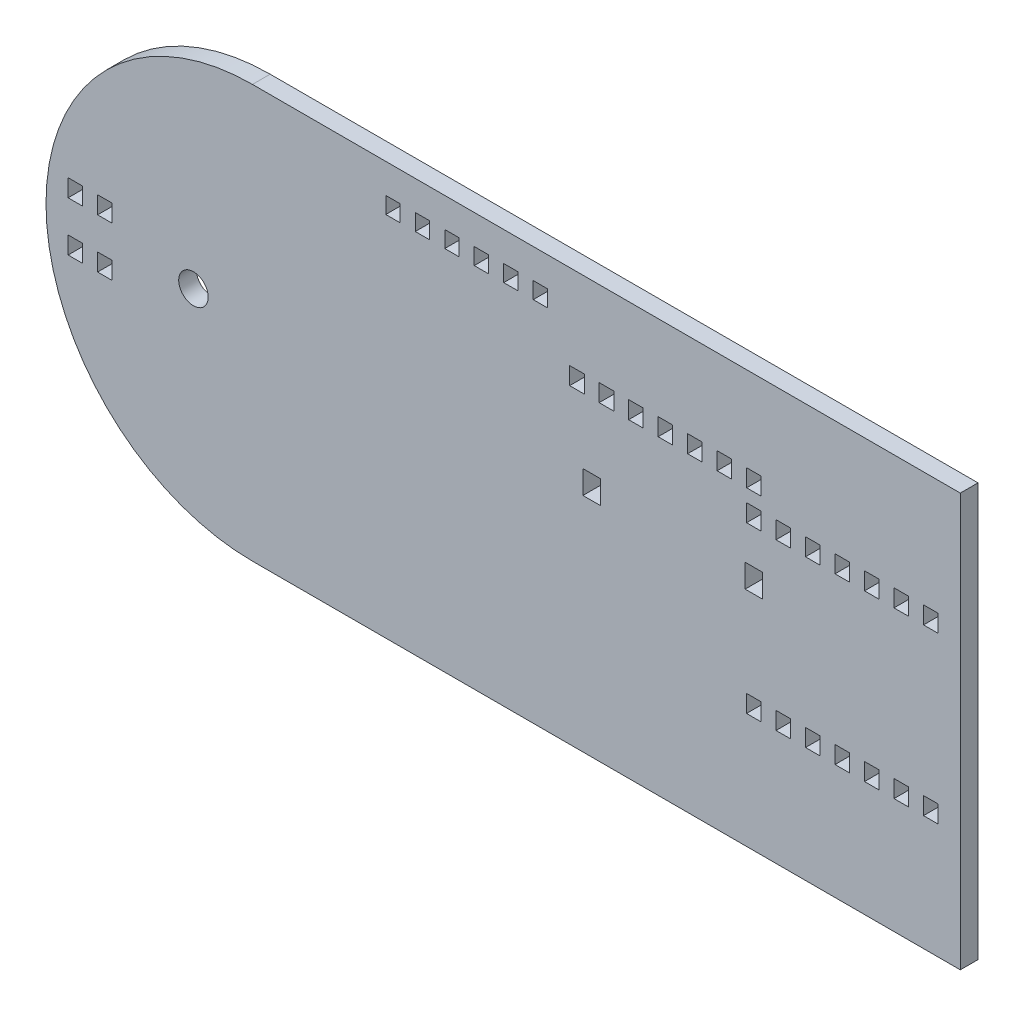
SolidWorks part; units mm, degrees
ref_plane "Plan de face" through (0, 0, 0) normal (0, 0, 1) x (1, 0, 0)
ref_plane "Plan de dessus" through (0, 0, 0) normal (0, 1, 0) x (1, 0, 0)
ref_plane "Plan de droite" through (0, 0, 0) normal (1, 0, 0) x (0, 0, -1)
sketch "Esquisse1" plane through (0, 0, 0) normal (0, 0, 1) x (1, 0, 0)
  line L1 (0, 0) -> (310, 0)
  line L2 (0, 0) -> (0, 140)
  line L3 (0, 140) -> (310, 140)
  line L4 (310, 0) -> (310, 140)
  line L29 (0, 70) -> (385.1323, 70) construction
  dimension "D1" = 140
  dimension "D10" = 310
extrude "Boss.-Extru.1" add sketch "Esquisse1" along normal blind 6
sketch "Esquisse4" plane through (0, 0, 6) normal (0, 0, 1) x (1, 0, 0)
  line L0 (0, 70) -> (310, 70) construction
  line L1 (0, 140) -> (0, 0) construction
  line L2 (310, 0) -> (310, 140) construction
  line L3 (187.55, 111.22) -> (187.55, 105.32)
  line L4 (182.05, 83.22) -> (187.95, 83.22)
  line L5 (182.05, 83.22) -> (182.05, 75.32)
  line L6 (182.05, 75.32) -> (187.95, 75.32)
  line L7 (187.95, 83.22) -> (187.95, 75.32)
  line L8 (237.05, 83.22) -> (242.95, 83.22)
  line L9 (237.05, 83.22) -> (237.05, 75.32)
  line L10 (237.05, 75.32) -> (242.95, 75.32)
  line L11 (242.95, 83.22) -> (242.95, 75.32)
  line L12 (185, 83.22) -> (185, 75.32) construction
  line L13 (240, 83.22) -> (240, 75.32) construction
  line L15 (182.05, 79.27) -> (232.95, 79.27) construction
  line L16 (177.55, 108.27) -> (182.5, 108.27) construction
  line L17 (177.55, 111.22) -> (182.5, 111.22)
  line L18 (177.55, 111.22) -> (177.55, 105.32)
  line L19 (177.55, 105.32) -> (182.5, 105.32)
  line L20 (182.5, 111.22) -> (182.5, 105.32)
  line L21 (187.55, 111.22) -> (192.5, 111.22)
  line L22 (180.025, 111.22) -> (180.025, 105.32) construction
  line L23 (192.5, 111.22) -> (192.5, 105.32)
  line L24 (187.55, 105.32) -> (192.5, 105.32)
  line L25 (197.55, 111.22) -> (197.55, 105.32)
  line L26 (197.55, 111.22) -> (202.5, 111.22)
  line L27 (202.5, 111.22) -> (202.5, 105.32)
  line L28 (197.55, 105.32) -> (202.5, 105.32)
  line L29 (207.55, 111.22) -> (207.55, 105.32)
  line L30 (207.55, 111.22) -> (212.5, 111.22)
  line L31 (212.5, 111.22) -> (212.5, 105.32)
  line L32 (207.55, 105.32) -> (212.5, 105.32)
  line L33 (217.55, 111.22) -> (217.55, 105.32)
  line L34 (217.55, 111.22) -> (222.5, 111.22)
  line L35 (222.5, 111.22) -> (222.5, 105.32)
  line L36 (217.55, 105.32) -> (222.5, 105.32)
  line L37 (227.55, 111.22) -> (227.55, 105.32)
  line L38 (227.55, 111.22) -> (232.5, 111.22)
  line L39 (232.5, 111.22) -> (232.5, 105.32)
  line L40 (227.55, 105.32) -> (232.5, 105.32)
  line L41 (237.55, 111.22) -> (237.55, 105.32)
  line L42 (237.55, 111.22) -> (242.5, 111.22)
  line L43 (242.5, 111.22) -> (242.5, 105.32)
  line L44 (237.55, 105.32) -> (242.5, 105.32)
  dimension "D1" = 5.9
  dimension "D2" = 7.9
  dimension "D3" = 38.27
  dimension "D4" = 70
  dimension "D5" = 55
  dimension "D6" = 7.9
  dimension "D7" = 5.9
  dimension "D9" = 5.9
  dimension "D10" = 4.95
  dimension "D11" = 29
  dimension "D12" = 4.975
  dimension "D13" = 7
  dimension "D14" = 5.05
extrude "Enlèv. mat.-Extru.3" cut sketch "Esquisse4" against normal blind 6
sketch "Esquisse5" plane through (0, 0, 0) normal (0, 0, -1) x (-1, 0, 0)
  line L0 (-302.475, 98) -> (-297.525, 98) construction
  line L1 (-302.475, 100.95) -> (-297.525, 100.95)
  line L2 (-302.475, 100.95) -> (-302.475, 95.05)
  line L3 (-302.475, 95.05) -> (-297.525, 95.05)
  line L4 (-297.525, 100.95) -> (-297.525, 95.05)
  line L5 (-292.475, 100.95) -> (-292.475, 95.05)
  line L6 (-300, 95.05) -> (-300, 100.95) construction
  line L7 (-292.475, 100.95) -> (-287.525, 100.95)
  line L8 (-287.525, 100.95) -> (-287.525, 95.05)
  line L9 (-292.475, 95.05) -> (-287.525, 95.05)
  line L10 (-282.475, 100.95) -> (-282.475, 95.05)
  line L11 (-282.475, 100.95) -> (-277.525, 100.95)
  line L12 (-277.525, 100.95) -> (-277.525, 95.05)
  line L13 (-282.475, 95.05) -> (-277.525, 95.05)
  line L14 (-272.475, 100.95) -> (-272.475, 95.05)
  line L15 (-272.475, 100.95) -> (-267.525, 100.95)
  line L16 (-267.525, 100.95) -> (-267.525, 95.05)
  line L17 (-272.475, 95.05) -> (-267.525, 95.05)
  line L18 (-262.475, 100.95) -> (-262.475, 95.05)
  line L19 (-262.475, 100.95) -> (-257.525, 100.95)
  line L20 (-257.525, 100.95) -> (-257.525, 95.05)
  line L21 (-262.475, 95.05) -> (-257.525, 95.05)
  line L22 (-252.475, 100.95) -> (-252.475, 95.05)
  line L23 (-252.475, 100.95) -> (-247.525, 100.95)
  line L24 (-247.525, 100.95) -> (-247.525, 95.05)
  line L25 (-252.475, 95.05) -> (-247.525, 95.05)
  line L26 (-242.475, 100.95) -> (-242.475, 95.05)
  line L27 (-242.475, 100.95) -> (-237.525, 100.95)
  line L28 (-237.525, 100.95) -> (-237.525, 95.05)
  line L29 (-242.475, 95.05) -> (-237.525, 95.05)
  line L31 (-310, 70) -> (0, 70) construction
  line L32 (-310, 0) -> (-310, 140) construction
  line L33 (0, 140) -> (0, 0) construction
  line L34 (-242.475, 39.05) -> (-237.525, 39.05)
  line L35 (-237.525, 39.05) -> (-237.525, 44.95)
  line L36 (-242.475, 44.95) -> (-237.525, 44.95)
  line L37 (-242.475, 39.05) -> (-242.475, 44.95)
  line L38 (-252.475, 39.05) -> (-247.525, 39.05)
  line L39 (-247.525, 39.05) -> (-247.525, 44.95)
  line L40 (-252.475, 44.95) -> (-247.525, 44.95)
  line L41 (-252.475, 39.05) -> (-252.475, 44.95)
  line L42 (-262.475, 39.05) -> (-257.525, 39.05)
  line L43 (-257.525, 39.05) -> (-257.525, 44.95)
  line L44 (-262.475, 44.95) -> (-257.525, 44.95)
  line L45 (-262.475, 39.05) -> (-262.475, 44.95)
  line L46 (-272.475, 39.05) -> (-267.525, 39.05)
  line L47 (-267.525, 39.05) -> (-267.525, 44.95)
  line L48 (-272.475, 44.95) -> (-267.525, 44.95)
  line L49 (-272.475, 39.05) -> (-272.475, 44.95)
  line L50 (-282.475, 39.05) -> (-277.525, 39.05)
  line L51 (-277.525, 39.05) -> (-277.525, 44.95)
  line L52 (-282.475, 44.95) -> (-277.525, 44.95)
  line L53 (-282.475, 39.05) -> (-282.475, 44.95)
  line L54 (-302.475, 44.95) -> (-297.525, 44.95)
  line L55 (-297.525, 39.05) -> (-297.525, 44.95)
  line L56 (-302.475, 39.05) -> (-297.525, 39.05)
  line L57 (-302.475, 39.05) -> (-302.475, 44.95)
  line L58 (-292.475, 39.05) -> (-287.525, 39.05)
  line L59 (-287.525, 39.05) -> (-287.525, 44.95)
  line L60 (-292.475, 44.95) -> (-287.525, 44.95)
  line L61 (-292.475, 39.05) -> (-292.475, 44.95)
  dimension "D1" = 4.95
  dimension "D2" = 5.9
  dimension "D4" = 28
  dimension "D5" = 5.05
  dimension "D6" = 10
  dimension "D3" = 7
extrude "Enlèv. mat.-Extru.4" cut sketch "Esquisse5" against normal blind 6
sketch "Esquisse6" plane through (0, 0, 0) normal (0, 0, -1) x (-1, 0, 0)
  line L0 (-310, 70) -> (0, 70) construction
  line L1 (-310, 0) -> (-310, 140) construction
  line L2 (0, 140) -> (0, 0) construction
  line L3 (-12.45, 81.35) -> (-12.45, 75.45)
  line L4 (-22.45, 81.35) -> (-17.5, 81.35)
  line L5 (-22.45, 81.35) -> (-22.45, 75.45)
  line L6 (-22.45, 75.45) -> (-17.5, 75.45)
  line L7 (-17.5, 81.35) -> (-17.5, 75.45)
  line L12 (-12.45, 81.35) -> (-7.5, 81.35)
  line L13 (-7.5, 81.35) -> (-7.5, 75.45)
  line L14 (-12.45, 75.45) -> (-7.5, 75.45)
  line L15 (-22.45, 78.4) -> (-7.5, 78.4) construction
  line L16 (-182.05, 79.27) -> (-242.95, 79.27) construction
  line L17 (-9.975, 81.35) -> (-9.975, 75.45) construction
  line L18 (-182.05, 83.22) -> (-182.05, 75.32) construction
  line L19 (-19.975, 81.35) -> (-19.975, 75.45) construction
  line L20 (-242.95, 75.32) -> (-242.95, 83.22) construction
  line L21 (-12.45, 58.65) -> (-7.5, 58.65)
  line L22 (-7.5, 58.65) -> (-7.5, 64.55)
  line L23 (-12.45, 64.55) -> (-7.5, 64.55)
  line L24 (-12.45, 58.65) -> (-12.45, 64.55)
  line L25 (-22.45, 64.55) -> (-17.5, 64.55)
  line L26 (-17.5, 58.65) -> (-17.5, 64.55)
  line L27 (-22.45, 58.65) -> (-17.5, 58.65)
  line L28 (-22.45, 58.65) -> (-22.45, 64.55)
  line L29 (-22.45, 78.4) -> (-2.45, 78.4) construction
  line L30 (-12.5, 83.2808) -> (-12.5, 77.9587) construction
  point P26 (-212.5, 79.27)
  dimension "D1" = 4.95
  dimension "D2" = 5.9
  dimension "D4" = 5.05
  dimension "D5" = 8.4
  dimension "D6" = 200
  dimension "D7" = 20
  dimension "D8" = 7.475
  dimension "D3" = 2
extrude "Enlèv. mat.-Extru.5" cut sketch "Esquisse6" against normal blind 6
sketch "Esquisse7" plane through (0, 0, 0) normal (0, 0, -1) x (-1, 0, 0)
  line L0 (-310, 140) -> (0, 140) construction
  line L1 (0, 140) -> (0, 0) construction
  line L2 (0, 0) -> (-310, 0) construction
  line L3 (-70, 140) -> (0, 140)
  line L5 (0, 0) -> (-70, 0)
  line L6 (0, 140) -> (30, 140)
  line L7 (30, 140) -> (30, 0)
  line L8 (30, 0) -> (0, 0)
  arc A0 (-70, 0) -> (-70, 140) centre (-70, 70) ccw
  dimension "D1" = 30
extrude "Enlèv. mat.-Extru.6" cut sketch "Esquisse7" against normal blind 6
sketch "Esquisse8" plane through (0, 0, 6) normal (0, 0, 1) x (1, 0, 0)
  line L0 (0, 70) -> (310, 70) construction
  line L1 (310, 0) -> (310, 140) construction
  circle A0 centre (50, 70) radius 5
  arc A1 (70, 140) -> (70, 0) centre (70, 70) ccw construction
  dimension "D2" = 10
  dimension "D1" = 50
extrude "Enlèv. mat.-Extru.7" cut sketch "Esquisse8" against normal blind 6
sketch "Esquisse9" plane through (0, 0, 6) normal (0, 0, 1) x (1, 0, 0)
  line L0 (115.2, 124.4) -> (169.9892, 124.4) construction
  line L1 (115.2, 130) -> (120, 130)
  line L2 (115.2, 130) -> (115.2, 124.4)
  line L3 (115.2, 124.4) -> (120, 124.4)
  line L4 (120, 130) -> (120, 124.4)
  line L5 (130, 130) -> (130, 124.4)
  line L6 (125.2, 130) -> (130, 130)
  line L7 (125.2, 130) -> (125.2, 124.4)
  line L8 (125.2, 124.4) -> (130, 124.4)
  line L9 (140, 130) -> (140, 124.4)
  line L10 (135.2, 130) -> (140, 130)
  line L11 (135.2, 130) -> (135.2, 124.4)
  line L12 (135.2, 124.4) -> (140, 124.4)
  line L13 (150, 130) -> (150, 124.4)
  line L14 (145.2, 130) -> (150, 130)
  line L15 (145.2, 130) -> (145.2, 124.4)
  line L16 (145.2, 124.4) -> (150, 124.4)
  line L17 (160, 130) -> (160, 124.4)
  line L18 (155.2, 130) -> (160, 130)
  line L19 (155.2, 130) -> (155.2, 124.4)
  line L20 (155.2, 124.4) -> (160, 124.4)
  line L21 (310, 140) -> (70, 140) construction
  line L22 (310, 0) -> (310, 140) construction
  line L23 (165.2, 130) -> (165.2, 124.4)
  line L24 (165.2, 130) -> (170, 130)
  line L25 (170, 130) -> (170, 124.4)
  line L26 (165.2, 124.4) -> (170, 124.4)
  dimension "D1" = 5.6
  dimension "D2" = 4.8
  dimension "D4" = 10
  dimension "D5" = 150
  dimension "D6" = 5.2
  dimension "D7" = 2
  dimension "D8" = 5.2
  dimension "D3" = 5
extrude "Enlèv. mat.-Extru.8" cut sketch "Esquisse9" against normal blind 10
